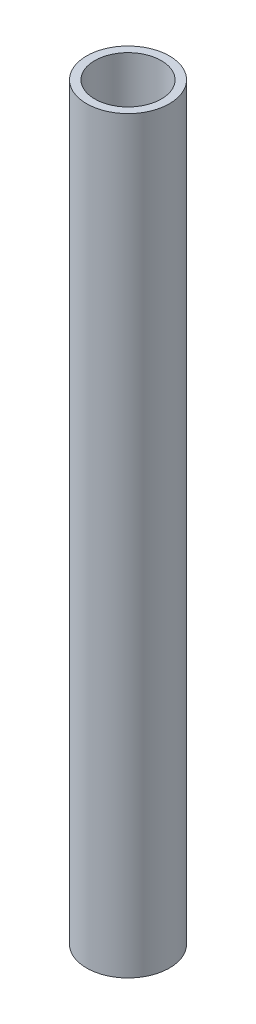
SolidWorks part; units mm, degrees
ref_plane "Front Plane" through (0, 0, 0) normal (0, 0, 1) x (1, 0, 0)
ref_plane "Top Plane" through (0, 0, 0) normal (0, 1, 0) x (1, 0, 0)
ref_plane "Right Plane" through (0, 0, 0) normal (1, 0, 0) x (0, 0, -1)
sketch "Sketch2" plane through (0, 0, 0) normal (0, 1, 0) x (1, 0, 0)
  circle A0 centre (0, 0) radius 10.395
  circle A1 centre (0, 0) radius 12.935
  dimension "D1" = 2.54
extrude "Boss-Extrude1" add sketch "Sketch2" along normal blind 233.68
